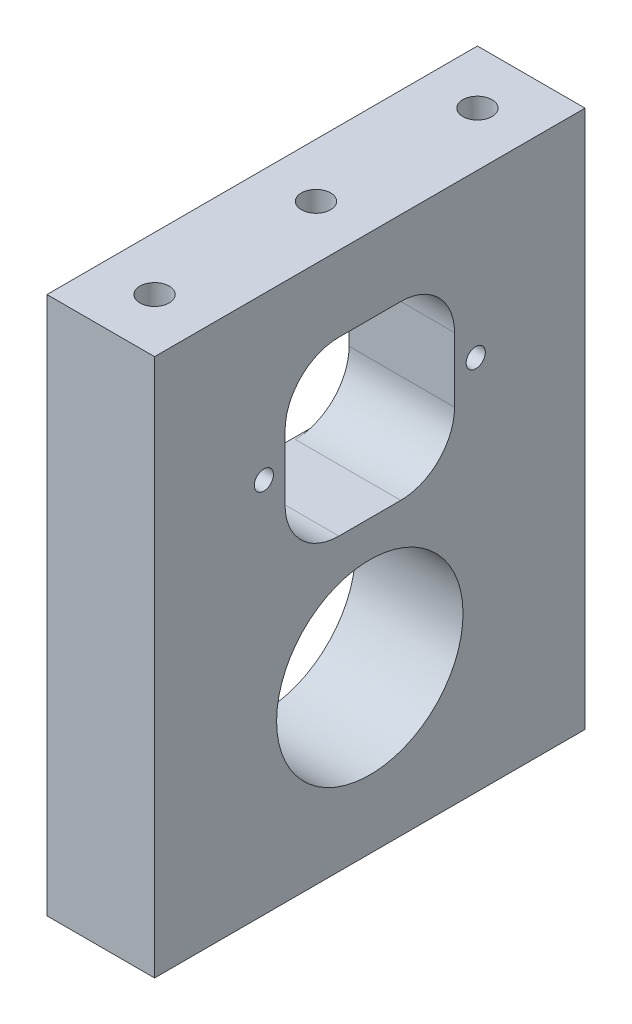
SolidWorks part; units mm, degrees
ref_plane "Front Plane" through (0, 0, 0) normal (0, 0, 1) x (1, 0, 0)
ref_plane "Top Plane" through (0, 0, 0) normal (0, 1, 0) x (1, 0, 0)
ref_plane "Right Plane" through (0, 0, 0) normal (1, 0, 0) x (0, 0, -1)
sketch "Sketch1" plane through (0, 0, 0) normal (1, 0, 0) x (0, 0, -1)
  line L1 (-25.4, -31.75) -> (25.4, -31.75)
  line L2 (-25.4, -31.75) -> (-25.4, 31.75)
  line L3 (-25.4, 31.75) -> (25.4, 31.75)
  line L4 (25.4, -31.75) -> (25.4, 31.75)
  line L5 (-25.4, -31.75) -> (25.4, 31.75) construction
  line L6 (-25.4, 31.75) -> (25.4, -31.75) construction
  point P0 (0, 0)
  dimension "D1" = 50.8
  dimension "D2" = 63.5
extrude "Boss-Extrude1" add sketch "Sketch1" along normal blind 12.7
hole_wizard "Ø22.0 (22) Diameter Hole1" positions "Sketch3" profile "Sketch2" hole size "Ø22.0" standard "ANSI Metric" end condition through all
sketch "Sketch3" plane through (12.7, 0, 0) normal (1, 0, 0) x (0, 0, -1)
  line L1 (25.4, 31.75) -> (-25.4, 31.75) construction
  line L2 (0, -31.75) -> (0, 31.75) construction
  line L3 (-25.4, -31.75) -> (25.4, -31.75) construction
  point P0 (0, -12.7)
  dimension "D1" = 44.45
sketch "Sketch2" plane through (12.7, -12.7, 0) normal (0, 1, 0) x (0, 0, -1)
  line L0 (0, 0) -> (0, 12.7)
  line L1 (0, 12.7) -> (11, 12.7)
  line L2 (11, 12.7) -> (11, 0)
  line L5 (11, 0) -> (0, 0)
  line L11 (0, -6.35) -> (0, 107.95) construction
  dimension "Thru Hole Dia." = 22
  dimension "Thru Hole Depth" = 12.7
hole_wizard "1/16 NPT Tapped Hole1" positions "Sketch5" profile "Sketch4" size "1/16" standard "ANSI Inch"
sketch "Sketch5" plane through (0, 0, 0) normal (-1, 0, 0) x (0, 0, 1)
  line L0 (25.4, -31.75) -> (-25.4, -31.75) construction
  circle A0 centre (0, -12.7) radius 11 construction
  point P0 (0, 12.7)
  point P5 (0, -31.75)
  dimension "D1" = 25.4
  dimension "D2" = 0
sketch "Sketch4" plane through (0, 12.7, 0) normal (0, 1, 0) x (0, 0, 1)
  line L0 (0, 0) -> (0, 13.5307)
  line L1 (3.0734, 11.684) -> (0, 13.5307)
  line L2 (-3.0734, 11.684) -> (0, 13.5307) construction
  line L3 (3.0734, 11.684) -> (3.0734, 6.858)
  line L4 (3.0734, 6.858) -> (3.7626, 6.858)
  line L5 (3.7626, 6.858) -> (3.9679, 0)
  line L6 (-3.7626, 6.858) -> (-3.9679, 0) construction
  line L7 (3.9679, 0) -> (0, 0)
  line L8 (0, -6.35) -> (0, 107.95) construction
  line L11 (-3.0734, 6.858) -> (-3.7626, 6.858) construction
  dimension "Tap Drill Dia." = 6.1468
  dimension "Tap Drill Depth" = 11.684
  dimension "Thread Dia." = 7.9358
  dimension "Thread Angle" = 3.43
  dimension "Thread Depth" = 6.858
  dimension "Drill Angle" = 118
hole_wizard "#4-40 Tapped Hole1" positions "Sketch7" profile "Sketch6" tap size "#4-40" standard "ANSI Inch" end condition through all
sketch "Sketch7" plane through (12.7, 0, 0) normal (1, 0, 0) x (0, 0, -1)
  line L0 (35.4085, 12.7) -> (-36.5694, 12.7) construction
  line L1 (0, 23.5312) -> (0, 12.7) construction
  circle A1 centre (0, 12.7) radius 3.5877 construction
  circle A2 centre (0, 12.7) radius 3.5877
  point P0 (-12.5, 12.7)
  point P2 (12.5, 12.7)
  dimension "D1" = 25
sketch "Sketch6" plane through (12.7, 12.7, 12.5) normal (0, 1, 0) x (0, 0, -1)
  line L0 (0, 0) -> (0, 12.7)
  line L1 (0, 12.7) -> (1.1303, 12.7)
  line L2 (1.1303, 12.7) -> (1.1303, 0)
  line L5 (1.1303, 0) -> (0, 0)
  line L11 (0, -6.35) -> (0, 107.95) construction
  dimension "Thread Major Dia." = 2.2606
  dimension "Thru Tap Drill Depth" = 12.7
sketch "Sketch9" plane through (12.7, 0, 0) normal (1, 0, 0) x (0, 0, -1)
  line L1 (-3.65, 2.54) -> (3.65, 2.54)
  line L2 (-10, 8.89) -> (-10, 16.51)
  line L3 (-3.65, 22.86) -> (3.65, 22.86)
  line L4 (10, 8.89) -> (10, 16.51)
  line L5 (-10, 2.54) -> (10, 22.86) construction
  line L6 (-10, 22.86) -> (10, 2.54) construction
  arc A0 (3.65, 22.86) -> (10, 16.51) centre (3.65, 16.51) cw
  arc A1 (3.65, 2.54) -> (10, 8.89) centre (3.65, 8.89) ccw
  arc A2 (-10, 8.89) -> (-3.65, 2.54) centre (-3.65, 8.89) ccw
  arc A3 (-3.65, 22.86) -> (-10, 16.51) centre (-3.65, 16.51) ccw
  point P0 (0, 12.7)
  dimension "D1" = 6.35
  dimension "D2" = 10
  dimension "D3" = 10.16
extrude "Cut-Extrude1" cut sketch "Sketch9" against normal through all
sketch "Sketch10" plane through (0, 0, 0) normal (1, 0, 0) x (0, 0, -1)
  line L0 (-11.3697, 12.7) -> (25.4, 12.7) construction
  line L1 (-12.5, 2.54) -> (12.5, 2.54)
  line L2 (-18.85, 8.89) -> (-18.85, 16.51)
  line L3 (-12.5, 22.86) -> (12.5, 22.86)
  line L4 (18.85, 8.89) -> (18.85, 16.51)
  line L5 (-18.85, 2.54) -> (18.85, 22.86) construction
  line L6 (-18.85, 22.86) -> (18.85, 2.54) construction
  line L7 (25.4, -31.75) -> (25.4, 31.75) construction
  line L8 (0, -23.7) -> (0, 31.75) construction
  line L9 (25.4, 31.75) -> (-25.4, 31.75) construction
  circle A0 centre (-12.5, 12.7) radius 1.1303 construction
  circle A1 centre (0, -12.7) radius 11 construction
  arc A2 (12.5, 22.86) -> (18.85, 16.51) centre (12.5, 16.51) cw
  arc A3 (12.5, 2.54) -> (18.85, 8.89) centre (12.5, 8.89) ccw
  arc A4 (-12.5, 2.54) -> (-18.85, 8.89) centre (-12.5, 8.89) cw
  arc A5 (-18.85, 16.51) -> (-12.5, 22.86) centre (-12.5, 16.51) cw
  point P0 (0, 12.7)
  dimension "D1" = 6.35
  dimension "D3" = 6.35
  dimension "D2" = 10.16
extrude "Cut-Extrude2" cut sketch "Sketch10" along normal blind 0.254
hole_wizard "#8-32 Tapped Hole1" positions "Sketch12" profile "Sketch11" tap size "#8-32" standard "ANSI Inch"
sketch "Sketch12" plane through (0, 31.75, 0) normal (0, 1, 0) x (1, 0, 0)
  line L0 (6.35, 25.4) -> (6.35, -25.4) construction
  line L1 (12.7, 25.4) -> (0, 25.4) construction
  line L2 (12.7, -25.4) -> (0, -25.4) construction
  line L3 (12.7, 0) -> (0, 0) construction
  line L4 (12.7, 25.4) -> (12.7, -25.4) construction
  line L5 (0, 25.4) -> (0, -25.4) construction
  point P0 (6.35, 19.05)
  point P2 (6.35, -19.05)
  point P13 (6.35, 0)
  dimension "D1" = 6.35
  dimension "D2" = 6.35
sketch "Sketch11" plane through (6.35, 31.75, -19.05) normal (1, 0, 0) x (0, 0, 1)
  line L0 (0, 0) -> (0, 11.7058)
  line L1 (0, 11.7058) -> (1.7272, 10.668)
  line L2 (1.7272, 10.668) -> (1.7272, 0)
  line L5 (1.7272, 0) -> (0, 0)
  line L10 (0, 11.7058) -> (-1.7272, 10.668) construction
  line L11 (0, -6.35) -> (0, 107.95) construction
  dimension "Tap Drill Dia." = 3.4544
  dimension "Tap Drill Depth" = 10.668
  dimension "Drill Angle" = 118
